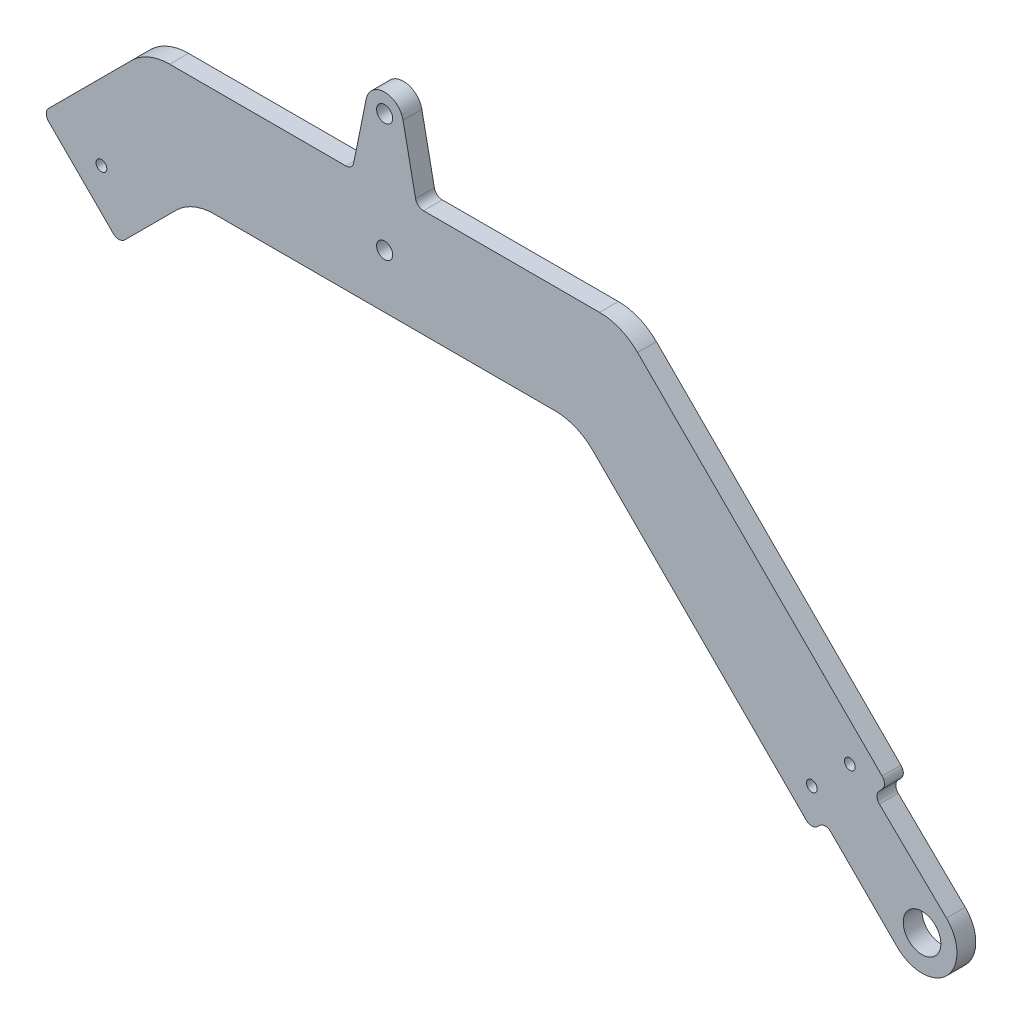
SolidWorks part; units mm, degrees
ref_plane "Front Plane" through (0, 0, 0) normal (0, 0, 1) x (1, 0, 0)
ref_plane "Top Plane" through (0, 0, 0) normal (0, 1, 0) x (1, 0, 0)
ref_plane "Right Plane" through (0, 0, 0) normal (1, 0, 0) x (0, 0, -1)
sketch "Sketch2" plane through (0, 0, 0) normal (0, 0, 1) x (1, 0, 0)
  line L0 (-100, 0) -> (100, 0) construction
  line L1 (-100, 0) -> (0, 100) construction
  line L2 (0, 100) -> (100, 0) construction
  line L3 (0, 0) -> (-52.6991, 47.3009) construction
  line L4 (-40, 60) -> (40, 60) construction
  line L5 (0, 100) -> (0, 60) construction
  circle A0 centre (-100, 0) radius 20
  circle A1 centre (0, 0) radius 20
  circle A2 centre (100, 0) radius 20
  point P2 (0, 0)
  dimension "D5" = 40
  dimension "D1" = 200
  dimension "D2" = 93.09
  dimension "D3" = 80
  dimension "D4" = 90
sketch "Sketch3" plane through (0, 0, 0) normal (0, 0, 1) x (1, 0, 0)
  line L0 (-40, 60) -> (-56.5165, 43.4835) construction
  line L1 (75.9584, 9.8995) -> (90.1005, 24.0416) construction
  line L2 (-40, 60) -> (40, 60) construction
  line L3 (40, 60) -> (86.565, 13.435) construction
  line L4 (0, 100) -> (100, 0) construction
  line L5 (86.565, 13.435) -> (40, 60) construction
  line L6 (-100, 0) -> (0, 100) construction
  line L7 (44.1421, 70) -> (93.636, 20.5061)
  line L8 (-44.1421, 70) -> (44.1421, 70)
  line L9 (-44.1421, 70) -> (-63.5876, 50.5546)
  line L10 (35.8579, 50) -> (79.4939, 6.364)
  line L11 (-35.8579, 50) -> (35.8579, 50)
  line L12 (-35.8579, 50) -> (-49.4454, 36.4124)
  line L13 (-63.5876, 50.5546) -> (-49.4454, 36.4124)
  line L14 (79.4939, 6.364) -> (93.636, 20.5061)
  line L15 (81.9688, 8.8388) -> (95.4038, -4.5962)
  line L16 (90.9809, 17.8509) -> (104.534, 4.6576)
  line L17 (-3.4304, 82.6944) -> (-6, 70)
  line L18 (0, 100) -> (0, 60) construction
  line L19 (3.4304, 82.6944) -> (6, 70)
  circle A0 centre (100, 0) radius 3.5
  circle A1 centre (100, 0) radius 10 construction
  arc A2 (95.4038, -4.5962) -> (104.534, 4.6576) centre (100, 0) ccw
  circle A3 centre (100, 0) radius 0.5
  circle A4 centre (100, 0) radius 20 construction
  circle A5 centre (100, 0) radius 6.5 construction
  circle A6 centre (79.4939, 13.435) radius 1
  circle A7 centre (86.565, 20.5061) radius 1
  circle A8 centre (0, 60) radius 1.5
  circle A11 centre (0, 82) radius 1.5
  arc A12 (3.4304, 82.6944) -> (-3.4304, 82.6944) centre (0, 82) ccw
  circle A13 centre (0, 82) radius 3.5 construction
  circle A14 centre (-52.6991, 47.3009) radius 1
  point P46 (79.4939, 13.435)
  dimension "D4" = 20
  dimension "D5" = 7
  dimension "D10" = 2
  dimension "D11" = 3
  dimension "D15" = 2
  dimension "D3" = 27.5
  dimension "D8" = 19
  dimension "D9" = 5
  dimension "D12" = 2
  dimension "D14" = 6
  dimension "D13" = 6
  dimension "D16" = 5
  dimension "D17" = 5
  dimension "D18" = 12
  dimension "D1" = 10
  dimension "D2" = 10
  dimension "D6" = 3
  dimension "D7" = 3
sketch "Sketch4" plane through (0, 0, 0) normal (0, 0, 1) x (1, 0, 0)
  line L0 (-100, 0) -> (100, 0) construction
  line L1 (-88.5703, 11.4297) -> (-52.6991, 47.3009) construction
  line L2 (-100, 0) -> (0, 100) construction
  line L3 (-52.6991, 47.3009) -> (-14.1397, 12.6913) construction
  line L4 (0, 0) -> (-52.6991, 47.3009) construction
  line L5 (-79.4939, 6.364) -> (-52.3277, 33.5302)
  line L6 (-52.3277, 33.5302) -> (-20.8193, 5.2493)
  line L7 (-93.636, 20.5061) -> (-53.0706, 61.0716)
  line L8 (-53.0706, 61.0716) -> (-7.4601, 20.1332)
  line L9 (-95.6414, 18.5007) -> (-53.0706, 61.0716) construction
  line L10 (-81.4993, 4.3586) -> (-52.3277, 33.5302) construction
  line L11 (-7.4601, 20.1332) -> (-20.8193, 5.2493)
  line L13 (-79.4939, 6.364) -> (-93.636, 20.5061)
  line L14 (-91.1612, 18.0312) -> (-104.5962, 4.5962)
  line L15 (-81.9688, 8.8388) -> (-95.4038, -4.5962)
  line L16 (-9.9683, 17.3388) -> (4.2763, 4.8952)
  line L17 (-18.4815, 7.854) -> (-4.3418, -4.8373)
  line L18 (9.9995, -0.1043) -> (10.0659, -0.1623)
  line L19 (-85.2086, 28.9335) -> (-71.0665, 14.7914) construction
  line L20 (-25.2845, 9.2571) -> (-11.9252, 24.141) construction
  circle A0 centre (-100, 0) radius 10 construction
  circle A1 centre (0, 0) radius 10 construction
  circle A6 centre (-100, 0) radius 3.5
  circle A7 centre (0, 0) radius 3.5
  arc A8 (-104.5962, 4.5962) -> (-95.4038, -4.5962) centre (-100, 0) ccw
  arc A9 (-4.3418, -4.8373) -> (4.2763, 4.8952) centre (0, 0) ccw
  circle A10 centre (0, 0) radius 20 construction
  circle A11 centre (0, 0) radius 6.5 construction
  circle A12 centre (-100, 0) radius 6.5 construction
  circle A13 centre (-81.6731, 25.398) radius 1
  circle A14 centre (-74.602, 18.3269) radius 1
  circle A15 centre (-21.9447, 12.9781) radius 1
  circle A16 centre (-15.2651, 20.42) radius 1
  dimension "D1" = 20
  dimension "D2" = 7
  dimension "D10" = 5
  dimension "D13" = 2
  dimension "D7" = 19
  dimension "D8" = 19
  dimension "D9" = 5
  dimension "D11" = 5
  dimension "D12" = 5
  dimension "D14" = 6
  dimension "D3" = 3
  dimension "D4" = 3
  dimension "D5" = 10
  dimension "D6" = 10
sketch "Sketch5" plane through (0, 0, 0) normal (0, 0, 1) x (1, 0, 0)
  line L13 (-44.1421, 70) -> (44.1421, 70)
  line L14 (44.1421, 70) -> (57.8914, 80.5)
  line L16 (57.8914, 80.5) -> (57.8914, 90.5)
  line L17 (57.8914, 90.5) -> (-57.1086, 90.5)
  line L18 (-57.1086, 90.5) -> (-57.1086, 80.5)
  line L19 (-57.1086, 80.5) -> (-44.1421, 70)
  line L20 (-4, 60) -> (-4, 70)
  line L21 (4, 60) -> (4, 70)
  line L22 (-22.5, 82) -> (22.5, 82) construction
  line L23 (0, 100) -> (0, 60) construction
  line L24 (-22.5, 86.5) -> (22.5, 86.5)
  line L25 (-22.5, 77.5) -> (22.5, 77.5)
  circle A0 centre (0, 60) radius 1.5 construction
  circle A1 centre (0, 60) radius 1.5
  arc A2 (-4, 60) -> (4, 60) centre (0, 60) ccw
  circle A3 centre (0, 60) radius 4 construction
  arc A4 (-22.5, 86.5) -> (-22.5, 77.5) centre (-22.5, 82) ccw
  arc A5 (22.5, 77.5) -> (22.5, 86.5) centre (22.5, 82) ccw
  point P21 (0, 82)
  point P26 (0, 0)
  dimension "D1" = 115
  dimension "D2" = 10
  dimension "D3" = 2.5
  dimension "D4" = 45
  dimension "D5" = 9
  dimension "D6" = 4
  dimension "D7" = 141
sketch "Sketch7" plane through (0, 0, 0) normal (0, 0, 1) x (1, 0, 0)
  line L0 (81.9688, 8.8388) -> (95.4038, -4.5962) construction
  line L1 (90.9809, 17.8509) -> (104.534, 4.6576) construction
  line L2 (-3.4304, 82.6944) -> (-6, 70) construction
  line L3 (3.4304, 82.6944) -> (6, 70) construction
  line L4 (81.9688, 8.8388) -> (95.4038, -4.5962)
  line L5 (90.9809, 17.8509) -> (104.534, 4.6576)
  line L6 (-3.4304, 82.6944) -> (-6, 70)
  line L7 (3.4304, 82.6944) -> (6, 70)
  line L8 (-49.4454, 36.4124) -> (-35.8579, 50)
  line L9 (-63.5876, 50.5546) -> (-49.4454, 36.4124)
  line L10 (-44.1421, 70) -> (-63.5876, 50.5546)
  line L11 (44.1421, 70) -> (-44.1421, 70)
  line L12 (93.636, 20.5061) -> (44.1421, 70)
  line L13 (79.4939, 6.364) -> (93.636, 20.5061)
  line L14 (35.8579, 50) -> (79.4939, 6.364)
  line L15 (-35.8579, 50) -> (35.8579, 50)
  line L16 (-49.4454, 36.4124) -> (-35.8579, 50)
  line L17 (-63.5876, 50.5546) -> (-49.4454, 36.4124)
  line L18 (-44.1421, 70) -> (-63.5876, 50.5546)
  line L19 (44.1421, 70) -> (6, 70)
  line L20 (93.636, 20.5061) -> (44.1421, 70)
  line L21 (79.4939, 6.364) -> (81.9688, 8.8388)
  line L22 (35.8579, 50) -> (79.4939, 6.364)
  line L23 (-35.8579, 50) -> (35.8579, 50)
  line L24 (90.9809, 17.8509) -> (93.636, 20.5061)
  line L25 (-6, 70) -> (-44.1421, 70)
  arc A0 (95.4038, -4.5962) -> (104.534, 4.6576) centre (100, 0) ccw construction
  circle A1 centre (100, 0) radius 0.5
  circle A2 centre (100, 0) radius 0.5
  circle A3 centre (100, 0) radius 3.5
  circle A4 centre (100, 0) radius 3.5
  circle A5 centre (0, 82) radius 1.5
  circle A6 centre (0, 82) radius 1.5
  circle A7 centre (0, 60) radius 1.5
  circle A8 centre (0, 60) radius 1.5
  circle A9 centre (86.565, 20.5061) radius 1
  circle A10 centre (86.565, 20.5061) radius 1
  circle A11 centre (79.4939, 13.435) radius 1
  circle A12 centre (79.4939, 13.435) radius 1
  circle A13 centre (-52.6991, 47.3009) radius 1
  circle A14 centre (-52.6991, 47.3009) radius 1
  arc A15 (3.4304, 82.6944) -> (-3.4304, 82.6944) centre (0, 82) ccw construction
  arc A16 (95.4038, -4.5962) -> (104.534, 4.6576) centre (100, 0) ccw
  arc A17 (3.4304, 82.6944) -> (-3.4304, 82.6944) centre (0, 82) ccw
  dimension "D1" = 0
  dimension "D2" = 0
  dimension "D3" = 0
  dimension "D4" = 0
  dimension "D5" = 0
  dimension "D6" = 0
  dimension "D7" = 0
  dimension "D8" = 0
extrude "Boss-Extrude2" add sketch "Sketch7" along normal blind 3.5 contours L7 A17 L6 L25 L18 L17 L16 L23 L22 L21 L4 A16 L5 L24 L20 L19 A4 A6 A8 A10 A12 A14
fillet "Fillet1" radius 10 4 edges at (35.8579, 50, 1.75) (-35.8579, 50, 1.75) (-44.1421, 70, 1.75) (44.1421, 70, 1.75)
fillet "Fillet2" radius 1.5 8 edges at (-49.4454, 36.4124, 1.75) (-63.5876, 50.5546, 1.75) (-6, 70, 1.75) (6, 70, 1.75) (90.9809, 17.8509, 1.75) (93.636, 20.5061, 1.75) (81.9688, 8.8388, 1.75) (79.4939, 6.364, 1.75)
